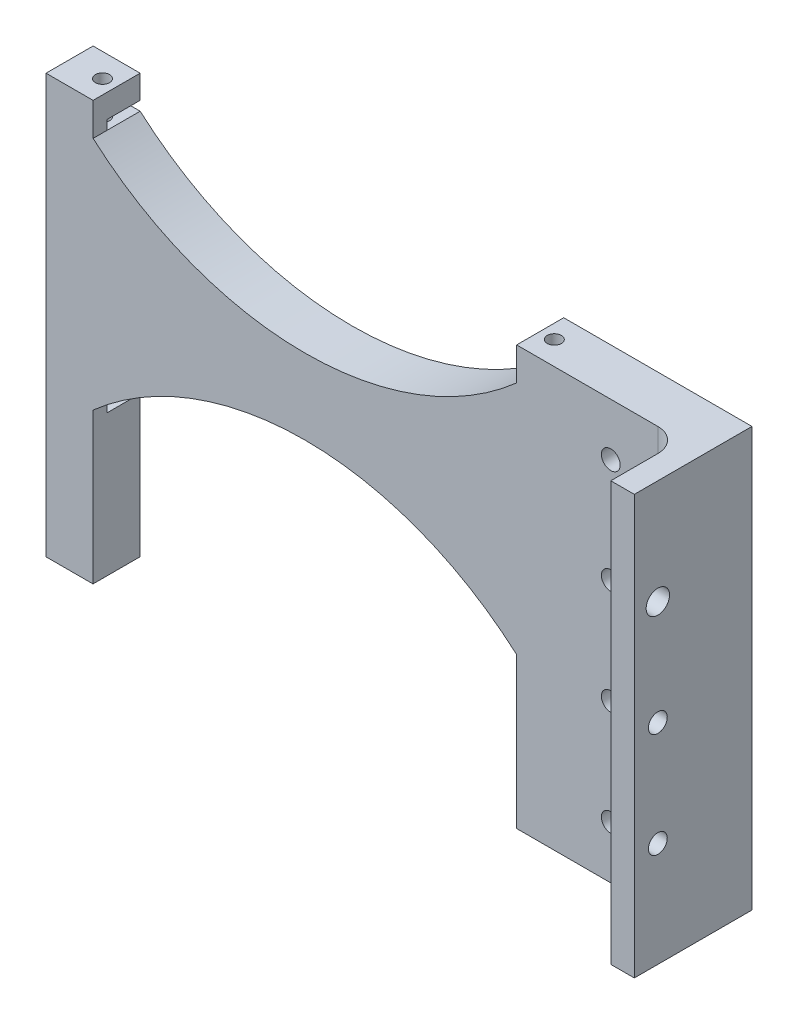
SolidWorks part; units mm, degrees
ref_plane "Front Plane" through (0, 0, 0) normal (0, 0, 1) x (1, 0, 0)
ref_plane "Top Plane" through (0, 0, 0) normal (0, 1, 0) x (1, 0, 0)
ref_plane "Right Plane" through (0, 0, 0) normal (1, 0, 0) x (0, 0, -1)
sketch "Sketch1" plane through (0, 0, 0) normal (0, 0, 1) x (1, 0, 0)
  line L1 (50, -25) -> (-50, -25)
  line L2 (50, -25) -> (50, 25)
  line L3 (50, 25) -> (-50, 25)
  line L4 (-50, -25) -> (-50, 25)
  line L5 (50, -25) -> (-50, 25) construction
  line L6 (50, 25) -> (-50, -25) construction
  arc A0 (-45, 25) -> (45, 25) centre (0, 76.0588) ccw
  arc A1 (-45.0185, -25) -> (45.0185, -25) centre (0, -76.1077) cw
  point P0 (0, 0)
  point P6 (-45, 25)
  point P7 (-45.0185, -25)
  point P8 (45, 25)
  point P9 (45.0185, -25)
  point P16 (0, -8)
  point P17 (0, 8)
  dimension "D1" = 50
  dimension "D2" = 100
  dimension "D3" = 5
  dimension "D4" = 5
  dimension "D5" = 8
  dimension "D6" = 8
extrude "Boss-Extrude1" add sketch "Sketch1" along normal blind 10 contours L1 A1 L2 L3 A0 L4
sketch "Sketch2" plane through (0, 25, 0) normal (0, 1, 0) x (1, 0, 0)
  line L0 (-50, -5) -> (50, -5) construction
  line L1 (-50, -10) -> (-50, 0) construction
  line L2 (50, -10) -> (50, 0) construction
  line L3 (-45, -10) -> (-45, 0) construction
  circle A0 centre (-48, -5) radius 1.5
  circle A1 centre (48, -5) radius 1.5
  point P7 (-48, -5)
  point P11 (48, -5)
  dimension "D2" = 96
  dimension "D3" = 3
extrude "Cut-Extrude1" cut sketch "Sketch2" against normal through all both and the other way through all
sketch "Sketch9" plane through (50, 0, 0) normal (1, 0, 0) x (0, 0, -1)
  line L1 (0, 25) -> (-10, 25)
  line L2 (0, 25) -> (0, -25)
  line L3 (0, -25) -> (-10, -25)
  line L4 (-10, 25) -> (-10, -25)
extrude "Boss-Extrude9" add sketch "Sketch9" along normal blind 5
sketch "Sketch10" plane through (-50, 0, 0) normal (-1, 0, 0) x (0, 0, 1)
  line L1 (10, -25) -> (0, -25)
  line L2 (10, -25) -> (10, 25)
  line L3 (10, 25) -> (0, 25)
  line L4 (0, -25) -> (0, 25)
extrude "Boss-Extrude10" add sketch "Sketch10" along normal blind 5
sketch "Sketch11" plane through (0, 25, 0) normal (0, 1, 0) x (1, 0, 0)
  line L0 (50, 0) -> (50, -7)
  line L1 (55, 0) -> (45, 0) construction
  line L2 (-50, 0) -> (-50, -7)
  line L3 (-45, 0) -> (-55, 0) construction
  line L4 (50, -7) -> (45, -7)
  line L5 (45, -10) -> (45, 0) construction
  line L6 (-50, -7) -> (-45, -7)
  line L7 (-45, -10) -> (-45, 0) construction
  line L8 (50, 0) -> (55, 0)
  line L9 (55, 0) -> (55, -10)
  line L10 (55, -10) -> (45, -10)
  line L11 (45, -10) -> (45, -7)
  line L12 (-45, -7) -> (-45, -10)
  line L13 (-45, -10) -> (-55, -10)
  line L14 (-55, -10) -> (-55, 0)
  line L15 (-55, 0) -> (-50, 0)
  circle A1 centre (48, -5) radius 1.5 construction
  circle A2 centre (-48, -5) radius 1.5 construction
  dimension "D1" = 100
  dimension "D2" = 2
  dimension "D3" = 2
extrude "Boss-Extrude11" add sketch "Sketch11" along normal blind 2
sketch "Sketch12" plane through (0, 27, 0) normal (0, 1, 0) x (1, 0, 0)
  line L0 (45, -7) -> (45, -10) construction
  line L1 (55, -10) -> (45, -10)
  line L2 (55, -10) -> (55, 0)
  line L3 (55, 0) -> (45, 0)
  line L4 (45, -10) -> (45, 0)
  line L6 (-55, -10) -> (-45, -10)
  line L7 (-55, -10) -> (-55, 0)
  line L8 (-55, 0) -> (-45, 0)
  line L9 (-45, -10) -> (-45, 0)
  dimension "D1" = 0
extrude "Boss-Extrude12" add sketch "Sketch12" along normal blind 5
sketch "Sketch13" plane through (0, 25, 0) normal (0, 1, 0) x (1, 0, 0)
  circle A0 centre (48, -5) radius 1.5
  circle A1 centre (-48, -5) radius 1.5
extrude "Cut-Extrude2" cut sketch "Sketch13" along normal up to surface (7 mm away) up to face at (-50, 32, 5)
sketch "Sketch14" plane through (0, -25, 0) normal (0, -1, 0) x (1, 0, 0)
  line L0 (50.0092, 0) -> (50.0092, 7)
  line L1 (55, 0) -> (45.0185, 0) construction
  line L2 (50.0092, 7) -> (45.0185, 7)
  line L3 (45.0185, 10) -> (45.0185, 0) construction
  line L4 (-50.0092, 0) -> (-50.0092, 7)
  line L5 (-45.0185, 0) -> (-55, 0) construction
  line L6 (-50.0092, 7) -> (-45.0185, 7)
  line L7 (-45.0185, 10) -> (-45.0185, 0) construction
  line L8 (-45.0185, 7) -> (-45.0185, 10)
  line L9 (-45.0185, 10) -> (-55, 10)
  line L10 (-55, 10) -> (-55, 0)
  line L11 (-55, 0) -> (-50.0092, 0)
  line L12 (45.0185, 7) -> (45.0185, 10)
  line L13 (45.0185, 10) -> (55, 10)
  line L14 (55, 10) -> (55, 0)
  line L15 (55, 0) -> (50.0092, 0)
  circle A0 centre (48, 5) radius 1.5 construction
  dimension "D1" = 2
extrude "Boss-Extrude13" add sketch "Sketch14" along normal blind 2
sketch "Sketch15" plane through (0, -27, 0) normal (0, -1, 0) x (1, 0, 0)
  line L1 (-55, 0) -> (-45.0185, 0)
  line L2 (-55, 0) -> (-55, 10)
  line L3 (-55, 10) -> (-45.0185, 10)
  line L4 (-45.0185, 0) -> (-45.0185, 10)
  line L5 (55, 10) -> (45.0185, 10)
  line L6 (55, 10) -> (55, 0)
  line L7 (55, 0) -> (45.0185, 0)
  line L8 (45.0185, 10) -> (45.0185, 0)
extrude "Boss-Extrude14" add sketch "Sketch15" along normal blind 30
sketch "Sketch16" plane through (0, -25, 0) normal (0, -1, 0) x (1, 0, 0)
  circle A1 centre (48, 5) radius 1.5
  circle A3 centre (-48, 5) radius 1.5
extrude "Cut-Extrude3" cut sketch "Sketch16" along normal up to surface (32 mm away) up to face at (-50.0092, -57, 5)
sketch "Sketch18" plane through (55, 0, 0) normal (1, 0, 0) x (0, 0, -1)
  line L1 (-10, 32) -> (0, 32)
  line L2 (-10, 32) -> (-10, -57)
  line L3 (-10, -57) -> (0, -57)
  line L4 (0, 32) -> (0, -57)
extrude "Boss-Extrude15" add sketch "Sketch18" along normal blind 30
sketch "Sketch19" plane through (0, 0, 10) normal (0, 0, 1) x (1, 0, 0)
  line L0 (85, -57) -> (45.0185, -57) construction
  line L1 (85, 32) -> (80, 32)
  line L2 (85, 32) -> (85, -57)
  line L3 (85, -57) -> (80, -57)
  line L4 (80, 32) -> (80, -57)
  dimension "D1" = 5
extrude "Boss-Extrude16" add sketch "Sketch19" along normal blind 15
fillet "Fillet1" radius 5 1 edges at (80, -12.5, 10)
sketch "Sketch20" plane through (80, 0, 0) normal (-1, 0, 0) x (0, 0, 1)
  line L0 (15, 32) -> (25, -57) construction
  line L1 (25, -57) -> (25, 32) construction
  line L2 (25, 32) -> (15, -57) construction
  line L3 (25, -57) -> (15, -57) construction
  line L4 (15, 32) -> (15, -57) construction
  line L5 (25, -12.5) -> (15, -57) construction
  line L6 (15, -57) -> (15, -12.5) construction
  line L7 (15, -12.5) -> (25, -57) construction
  line L8 (25, 32) -> (15, -12.5) construction
  line L9 (15, -12.5) -> (15, 32) construction
  line L10 (15, 32) -> (25, -12.5) construction
  circle A0 centre (20, 9.75) radius 2.4844
  circle A1 centre (20, -12.5) radius 2
  circle A2 centre (20, -34.75) radius 2
  point P12 (20, 9.75)
  point P14 (20, -12.5)
  point P15 (20, -34.75)
extrude "Cut-Extrude4" cut sketch "Sketch20" against normal through all
sketch "Sketch22" plane through (0, 0, 10) normal (0, 0, 1) x (1, 0, 0)
  line L0 (65, 9.75) -> (65, 32) construction
  line L5 (45, 32) -> (75, 32) construction
  line L7 (65, -12.5) -> (65, 9.75) construction
  line L8 (65, -34.75) -> (65, -12.5) construction
  line L9 (65, -34.75) -> (65, -57) construction
  line L10 (75, -57) -> (45.0185, -57) construction
  circle A0 centre (65, 20.875) radius 2
  circle A1 centre (65, -1.375) radius 2
  circle A2 centre (65, -23.625) radius 2
  circle A3 centre (65, -45.875) radius 2
  point P4 (65, 9.75)
  point P8 (65, -12.5)
  point P9 (65, -34.75)
extrude "Cut-Extrude5" cut sketch "Sketch22" against normal through all
